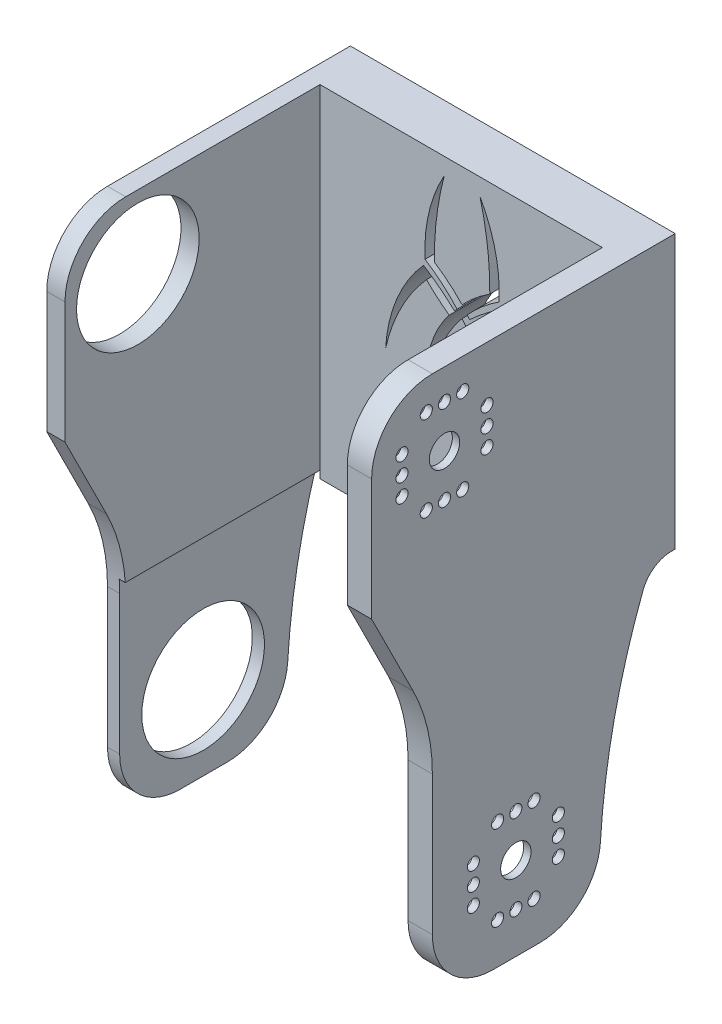
SolidWorks part; units mm, degrees
ref_plane "Front Plane" through (0, 0, 0) normal (0, 0, 1) x (1, 0, 0)
ref_plane "Top Plane" through (0, 0, 0) normal (0, 1, 0) x (1, 0, 0)
ref_plane "Right Plane" through (0, 0, 0) normal (1, 0, 0) x (0, 0, -1)
sketch "Sketch1" plane through (0, 0, 0) normal (0, 1, 0) x (1, 0, 0)
  line L0 (-27.5, 0) -> (-27.5, 42)
  line L1 (-27.5, 42) -> (19, 42)
  line L2 (19, 42) -> (19, 0)
  line L3 (19, 0) -> (23, 0)
  line L4 (23, 0) -> (23, 50)
  line L5 (23, 50) -> (-30.5, 50)
  line L6 (-30.5, 50) -> (-30.5, 0)
  line L7 (-30.5, 0) -> (-27.5, 0)
  dimension "D1" = 3
  dimension "D2" = 4
  dimension "D3" = 8
  dimension "D4" = 50
  dimension "D5" = 46.5
  dimension "D6" = 23
extrude "Boss-Extrude1" add sketch "Sketch1" along normal blind 90
sketch "Sketch2" plane through (19, 0, 0) normal (-1, 0, 0) x (0, 0, 1)
  line L0 (0, 90) -> (0, 0) construction
  line L1 (-50, 90) -> (0, 90) construction
  circle A0 centre (-12, 78) radius 10.1
  dimension "D1" = 20.2
  dimension "D2" = 12
  dimension "D3" = 12
extrude "Cut-Extrude1" cut sketch "Sketch2" against normal blind 2.8
sketch "Sketch3" plane through (21.8, 0, 0) normal (-1, 0, 0) x (0, 0, 1)
  line L0 (-50, 90) -> (0, 90) construction
  line L1 (0, 90) -> (0, 0) construction
  circle A0 centre (-12, 78) radius 10.1
  circle A1 centre (-12, 78) radius 2.5
  circle A2 centre (-12, 85) radius 1
  circle A3 centre (-15, 85) radius 1
  circle A4 centre (-9, 85) radius 1
  circle A5 centre (-5, 81) radius 1
  circle A6 centre (-5, 78) radius 1
  circle A7 centre (-5, 75) radius 1
  circle A8 centre (-9, 71) radius 1
  circle A9 centre (-12, 71) radius 1
  circle A10 centre (-15, 71) radius 1
  circle A11 centre (-19, 75) radius 1
  circle A12 centre (-19, 78) radius 1
  circle A13 centre (-19, 81) radius 1
  point P34 (-12, 78)
  dimension "D1" = 20.2
  dimension "D4" = 7
  dimension "D5" = 2
  dimension "D6" = 2
  dimension "D7" = 2
  dimension "D2" = 12
  dimension "D3" = 12
  dimension "D8" = 3
  dimension "D9" = 3
  dimension "D10" = 4
extrude "Cut-Extrude2" cut sketch "Sketch3" against normal blind 22 contours A1 | A3 | A2 | A4 | A13 | A12 | A11 | A10 | A9 | A8 | A7 | A6 | A5
sketch "Sketch4" plane through (-30.5, 0, 0) normal (-1, 0, 0) x (0, 0, 1)
  line L0 (0, 90) -> (0, 0) construction
  line L1 (-50, 90) -> (0, 90) construction
  circle A0 centre (-12, 78) radius 10.1
  dimension "D1" = 20.2
  dimension "D2" = 12
  dimension "D3" = 12
extrude "Cut-Extrude3" cut sketch "Sketch4" against normal blind 10
fillet "Fillet1" radius 10 2 edges at (-29, 90, 0) (21, 90, 0)
sketch "Sketch8" plane through (23, 0, 0) normal (1, 0, 0) x (0, 0, -1)
  line L0 (0, 0) -> (10, 0)
  line L1 (0, 0) -> (50, 0) construction
  line L2 (10, 0) -> (10, 40)
  line L3 (10, 40) -> (0, 60)
  line L4 (0, 80) -> (0, 0) construction
  line L5 (0, 60) -> (0, 0)
  line L6 (50, 45) -> (49.384, 45)
  line L7 (50, 90) -> (50, 0) construction
  line L8 (37.5, 0) -> (50, 0)
  line L9 (50, 0) -> (50, 45)
  arc A0 (44.7132, 41.7843) -> (37.5, 0) centre (147.4709, 2.5305) ccw
  arc A1 (49.384, 45) -> (44.7132, 41.7843) centre (49.384, 40) ccw
  point P19 (46, 45)
  dimension "D5" = 110
  dimension "D7" = 5
  dimension "D1" = 20
  dimension "D2" = 10
  dimension "D3" = 60
  dimension "D4" = 4
  dimension "D6" = 12.5
extrude "Cut-Extrude9" cut sketch "Sketch8" against normal blind 70
fillet "Fillet2" radius 30 2 edges at (-29, 40, -10) (21, 40, -10)
sketch "Sketch9" plane through (19, 0, 0) normal (-1, 0, 0) x (0, 0, 1)
  line L0 (-10, 0) -> (-10, 32.918) construction
  line L2 (-37.5, 0) -> (-10, 0) construction
  circle A0 centre (-23.75, 13.75) radius 10.1
  circle A1 centre (-23.75, 13.75) radius 2.5
  circle A2 centre (-23.75, 20.75) radius 1
  circle A3 centre (-26.75, 20.75) radius 1
  circle A4 centre (-20.75, 20.75) radius 1
  circle A5 centre (-16.75, 10.75) radius 1
  circle A6 centre (-16.75, 13.75) radius 1
  circle A7 centre (-16.75, 16.75) radius 1
  circle A8 centre (-26.75, 6.75) radius 1
  circle A9 centre (-23.75, 6.75) radius 1
  circle A10 centre (-20.75, 6.75) radius 1
  circle A11 centre (-30.75, 16.75) radius 1
  circle A12 centre (-30.75, 13.75) radius 1
  circle A13 centre (-30.75, 10.75) radius 1
  point P34 (-23.75, 13.75)
  dimension "D1" = 20.2
  dimension "D5" = 2
  dimension "D8" = 5
  dimension "D2" = 7
  dimension "D3" = 13.75
  dimension "D4" = 13.75
  dimension "D6" = 3
  dimension "D7" = 3
  dimension "D9" = 4
extrude "Cut-Extrude11" cut sketch "Sketch9" against normal blind 22.8 contours A7 | A4 | A6 | A5 | A10 | A9 | A8 | A13 | A12 | A11 | A3 | A2 | A1 | A0
sketch "Sketch10" plane through (19, 0, 0) normal (-1, 0, 0) x (0, 0, 1)
  line L0 (-10, 0) -> (-10, 32.918) construction
  line L1 (-37.5, 0) -> (-10, 0) construction
  circle A0 centre (-23.75, 13.75) radius 10.1
  dimension "D1" = 20.2
  dimension "D2" = 13.75
  dimension "D3" = 13.75
extrude "Cut-Extrude12" cut sketch "Sketch10" against normal blind 2.8
sketch "Sketch11" plane through (-30.5, 0, 0) normal (-1, 0, 0) x (0, 0, 1)
  line L0 (-10, 0) -> (-10, 32.918) construction
  line L2 (-37.5, 0) -> (-10, 0) construction
  circle A0 centre (-23.75, 13.75) radius 10.1
  dimension "D1" = 20.2
  dimension "D3" = 13.75
  dimension "D2" = 13.75
extrude "Cut-Extrude13" cut sketch "Sketch11" against normal blind 12.8
fillet "Fillet4" radius 10 4 edges at (21, 0, -10) (21, 0, -37.5) (-29, 0, -10) (-29, 0, -37.5)
sketch "Sketch13" plane through (0, 0, 0) normal (0, 0, 1) x (1, 0, 0)
  line L0 (-27.5, 32.918) -> (-27.5, 10) construction
  line L1 (-28.5, 0) -> (-27.5, 0)
  line L2 (-28.5, 0) -> (-28.5, 35)
  line L3 (-28.5, 35) -> (-27.5, 35)
  line L4 (-27.5, 0) -> (-27.5, 35)
  dimension "D1" = 1
  dimension "D2" = 35
  dimension "D3" = 0
extrude "Cut-Extrude14" cut sketch "Sketch13" against normal blind 50
sketch "Sketch14" plane through (0, 0, -50) normal (0, 0, -1) x (-1, 0, 0)
  line L0 (3.2778, 69.2509) -> (2.8452, 68.8017)
  line L2 (4.9309, 69.2509) -> (5.3635, 68.8017)
  arc A0 (1.1666, 87.2263) -> (-0.4611, 74.0943) centre (49.126, 74.6146) ccw
  arc A1 (4.1043, 70.2931) -> (-0.4611, 74.0943) centre (-13.8284, 53.3972) ccw
  arc A2 (1.1666, 87.2263) -> (-1.9905, 73.733) centre (22.8881, 75.0279) ccw
  arc A3 (3.2778, 69.2509) -> (-1.9905, 73.733) centre (-16.0734, 51.8426) ccw
  arc A4 (2.8452, 68.8017) -> (-2.2463, 72.7451) centre (-20.692, 43.6705) ccw
  arc A5 (-2.2463, 72.7451) -> (-8.488, 57.7998) centre (16.199, 56.2656) ccw
  arc A6 (-8.488, 57.7998) -> (-1.768, 70.9335) centre (20.3265, 51.3428) cw
  arc A7 (-1.768, 70.9335) -> (1.9716, 67.7438) centre (22.4978, 95.5961) ccw
  arc A8 (1.9716, 67.7438) -> (-0.654, 50.2835) centre (16.0244, 56.7031) ccw
  arc A9 (-0.654, 50.2835) -> (4.1043, 68.3286) centre (20.791, 54.2785) cw
  arc A10 (8.8627, 50.2835) -> (4.1043, 68.3286) centre (-12.5824, 54.2785) ccw
  arc A11 (6.237, 67.7438) -> (8.8627, 50.2835) centre (-7.8158, 56.7031) cw
  arc A12 (9.9767, 70.9335) -> (6.237, 67.7438) centre (-14.2892, 95.5961) cw
  arc A13 (16.6966, 57.7998) -> (9.9767, 70.9335) centre (-12.1178, 51.3428) ccw
  arc A14 (10.4549, 72.7451) -> (16.6966, 57.7998) centre (-7.9903, 56.2656) cw
  arc A15 (5.3635, 68.8017) -> (10.4549, 72.7451) centre (28.9006, 43.6705) cw
  arc A16 (4.9309, 69.2509) -> (10.1992, 73.733) centre (24.282, 51.8426) cw
  arc A17 (4.1043, 70.2931) -> (8.6698, 74.0943) centre (22.0371, 53.3972) cw
  arc A18 (7.042, 87.2263) -> (10.1992, 73.733) centre (-14.6794, 75.0279) cw
  arc A19 (7.042, 87.2263) -> (8.6698, 74.0943) centre (-40.9173, 74.6146) cw
extrude "Cut-Extrude20" cut sketch "Sketch14" against normal blind 20
